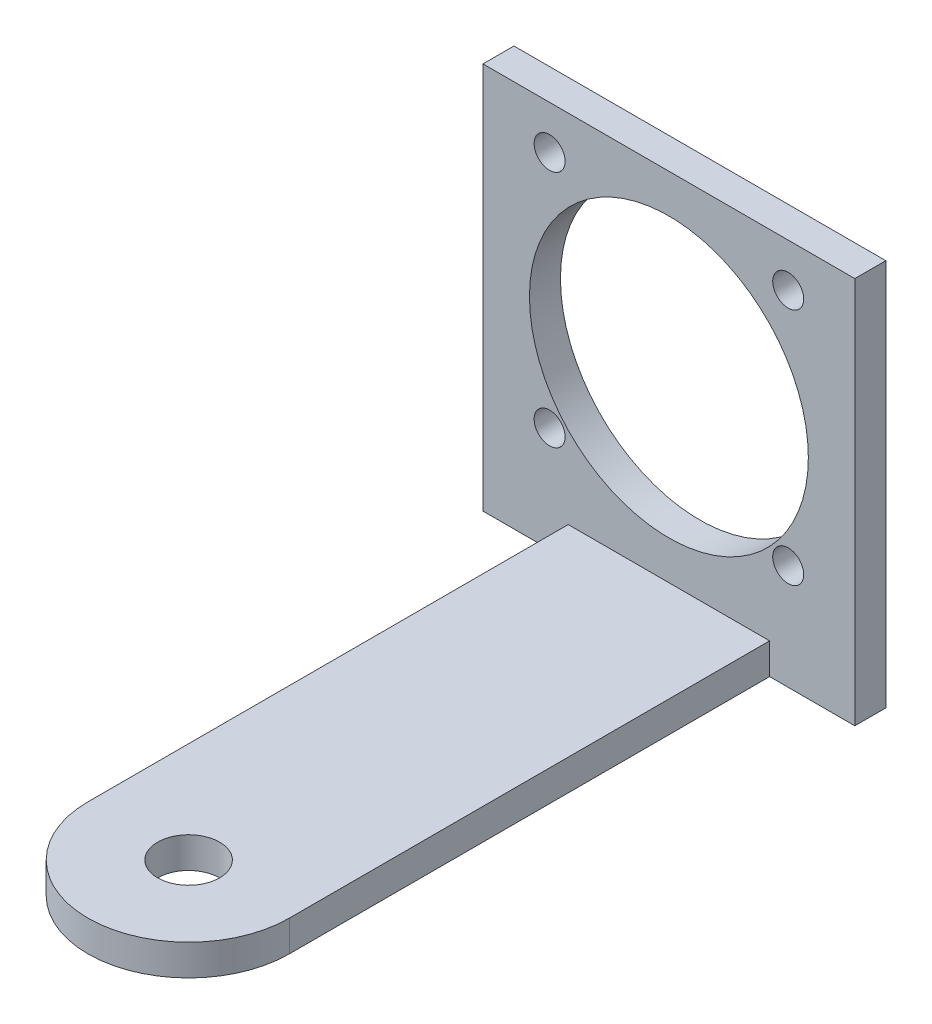
SolidWorks part; units mm, degrees
material "3.0205 (EN-AW 1200)"
ref_plane "前视基准面" through (0, 0, 0) normal (0, 0, 1) x (1, 0, 0)
ref_plane "上视基准面" through (0, 0, 0) normal (0, 1, 0) x (1, 0, 0)
ref_plane "右视基准面" through (0, 0, 0) normal (1, 0, 0) x (0, 0, -1)
sketch "草图1" plane through (0, 0, 0) normal (0, 1, 0) x (1, 0, 0)
  line L1 (5, 0) -> (2.5, 4.3301)
  line L2 (2.5, 4.3301) -> (-2.5, 4.3301)
  line L3 (-2.5, 4.3301) -> (-5, 0)
  line L4 (-5, 0) -> (-2.5, -4.3301)
  line L5 (-2.5, -4.3301) -> (2.5, -4.3301)
  line L6 (5, 0) -> (2.5, -4.3301)
sketch "草图2" plane through (0, 0, 0) normal (0, 1, 0) x (1, 0, 0)
  circle A0 centre (0, 0) radius 6.5
extrude "凸台-拉伸1" add sketch "草图2" along normal blind 2
sketch "草图3" plane through (0, 2, 0) normal (0, 1, 0) x (1, 0, 0)
  circle A0 centre (0, 0) radius 2
extrude "切除-拉伸2" cut sketch "草图3" against normal through all
sketch "草图4" plane through (0, 2, 0) normal (0, 1, 0) x (1, 0, 0)
  line L1 (6.5, 31) -> (3.8991, 31)
  line L3 (-6.5, 0) -> (-6.5, 31)
  line L4 (-6.5, 31) -> (-4.1009, 31)
  line L7 (-6.5, 0) -> (6.5, 0)
  line L8 (6.5, 0) -> (6.5, 31)
  line L11 (-4.1009, 31) -> (3.8991, 31)
  circle A0 centre (0, 0) radius 6.5 construction
  circle A1 centre (0, 0) radius 6.5
extrude "凸台-拉伸2" add sketch "草图4" against normal blind 2
sketch "草图6" plane through (0, 0, -31) normal (0, 0, -1) x (-1, 0, 0)
  line L5 (-15.5564, 5.1908) -> (-3.328, -1.1893)
sketch "草图18" plane through (0, 0, 0) normal (0, -1, 0) x (1, 0, 0)
  circle A0 centre (0, 0) radius 2.5328
sketch "草图20" plane through (0, 0, 0) normal (1, 0, 0) x (0, 0, -1)
  line L0 (0, 2) -> (0, 3)
  circle A0 centre (0, 3) radius 1.5
sketch "草图21" plane through (0, 0, -31) normal (0, 0, -1) x (-1, 0, 0)
  line L0 (0, 0) -> (12, 0)
  line L1 (12, 0) -> (12, 25)
  line L2 (12, 25) -> (-12, 25)
  line L3 (-12, 25) -> (-12, 0)
  line L4 (-12, 0) -> (0, 0)
extrude "凸台-拉伸3" add sketch "草图21" along normal blind 2
sketch "草图22" plane through (0, 0, -31) normal (0, 0, 1) x (1, 0, 0)
  line L0 (-6.5, 2) -> (-12, 2)
  line L1 (-12, 0) -> (-12, 25) construction
  line L2 (0, 2) -> (0, 25)
  line L3 (-6.5, 2) -> (6.5, 2) construction
  line L4 (-12, 25) -> (12, 25) construction
  line L5 (0, 13.5) -> (7.7, 13.5)
  line L6 (7.7, 13.5) -> (7.7, 22.2)
  line L7 (7.7, 22.2) -> (-7.7, 22.2)
  line L8 (-7.7, 22.2) -> (-7.7, 6.8)
  line L9 (-7.7, 6.8) -> (7.7, 6.8)
  circle A0 centre (0, 13.5) radius 9
  circle A1 centre (7.7, 22.2) radius 1
  circle A2 centre (-7.7, 22.2) radius 1
  circle A3 centre (-7.7, 6.8) radius 1
  circle A4 centre (7.7, 6.8) radius 1
extrude "切除-拉伸4" cut sketch "草图22" against normal blind 2 contours A0 | A3 | A4 | A1 | A2
